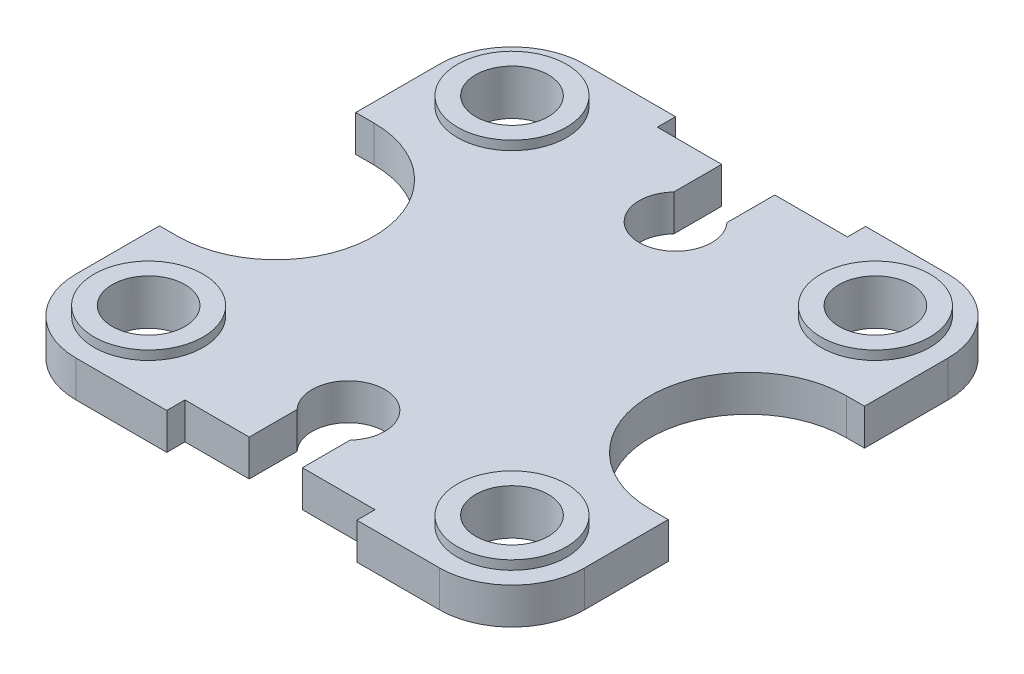
SolidWorks part; units mm, degrees
ref_plane "Front Plane" through (0, 0, 0) normal (0, 0, 1) x (1, 0, 0)
ref_plane "Top Plane" through (0, 0, 0) normal (0, 1, 0) x (1, 0, 0)
ref_plane "Right Plane" through (0, 0, 0) normal (1, 0, 0) x (0, 0, -1)
sketch "Sketch2" plane through (0, 0, 0) normal (0, 1, 0) x (1, 0, 0)
  line L0 (-169.9831, 0) -> (-150, 0) construction
  line L1 (-100, 140) -> (-50, 140)
  line L2 (-140, 100) -> (-140, 54)
  line L3 (-100, -140) -> (-50, -140)
  line L4 (140, 100) -> (140, 54)
  line L5 (-140, 140) -> (140, -140) construction
  line L6 (-140, -140) -> (140, 140) construction
  line L7 (-140, 0) -> (165.6353, 0) construction
  line L8 (-140, 54) -> (-130, 54)
  line L10 (-140, -54) -> (-130, -54)
  line L11 (-130, 54) -> (-130, 0)
  line L12 (-150, 54) -> (-130, -54) construction
  line L13 (-140, 0) -> (-130, 54) construction
  line L14 (-140, -54) -> (-140, -100)
  line L15 (0, 140) -> (0, -140) construction
  line L16 (140, -54) -> (130, -54)
  line L18 (140, 54) -> (130, 54)
  line L19 (140, -54) -> (140, -100)
  line L20 (54.6115, 140) -> (100, 140)
  line L22 (-50, 140) -> (-50, 130)
  line L23 (-50, 130) -> (-14.6115, 130)
  line L24 (54.6115, 140) -> (54.6115, 130)
  line L25 (-45.701, 148.3684) -> (54.6115, 130) construction
  line L26 (-50, 130) -> (54.2681, 150.8536) construction
  line L27 (14.6115, 130) -> (14.6115, 103.6567)
  line L28 (-14.6115, 130) -> (-14.6115, 103.6567)
  line L29 (54.6115, -140) -> (54.6115, -130)
  line L30 (-50, -140) -> (-50, -130)
  line L31 (-50, -130) -> (-14.6115, -130)
  line L32 (14.6115, -130) -> (14.6115, -103.6567)
  line L33 (-14.6115, -130) -> (-14.6115, -103.6567)
  line L34 (14.6115, 130) -> (54.6115, 130)
  line L35 (14.6115, -130) -> (54.6115, -130)
  line L36 (54.6115, -140) -> (100, -140)
  arc A0 (140, 100) -> (100, 140) centre (100, 100) ccw
  arc A1 (100, -140) -> (140, -100) centre (100, -100) ccw
  arc A2 (-100, -140) -> (-140, -100) centre (-100, -100) cw
  arc A3 (-100, 140) -> (-140, 100) centre (-100, 100) ccw
  arc A4 (-130, -54) -> (-130, 54) centre (-130, 0) ccw
  arc A5 (130, -54) -> (130, 54) centre (130, 0) cw
  circle A6 centre (-100, 100) radius 20
  circle A8 centre (100, 100) radius 20
  circle A9 centre (-100, -100) radius 20
  circle A10 centre (100, -100) radius 20
  arc A11 (-14.6115, 103.6567) -> (14.6115, 103.6567) centre (0, 90) ccw
  arc A12 (-14.6115, -103.6567) -> (14.6115, -103.6567) centre (0, -90) cw
  point P0 (0, 0)
  point P20 (-140, 0)
  dimension "D3" = 40
  dimension "D5" = 10
  dimension "D7" = 180
  dimension "D9" = 40
  dimension "D1" = 280
  dimension "D2" = 280
  dimension "D4" = 10
  dimension "D6" = 100
  dimension "D8" = 40
extrude "Boss-Extrude1" add sketch "Sketch2" along normal blind 20 contours L33 A12 L32 L35 L29 L36 A1 L19 L16 A5 L18 L4 A0 L20 L24 L34 L27 A11 L28 L23 L22 L1 A3 L2 L8 A4 L10 L14 A2 L3 L30 L31 A9 A6 A8 A10
sketch "Sketch3" plane through (0, 20, 0) normal (0, 1, 0) x (1, 0, 0)
  line L0 (0, 35.7741) -> (0, -24.3678) construction
  line L1 (-51.328, 0) -> (50.9824, 0) construction
  circle A0 centre (-100, 100) radius 30
  circle A1 centre (100, 100) radius 30
  circle A2 centre (100, -100) radius 30
  circle A3 centre (-100, -100) radius 30
  circle A4 centre (-100, 100) radius 20
  circle A5 centre (100, 100) radius 20
  circle A6 centre (100, -100) radius 20
  circle A7 centre (-100, -100) radius 20
  dimension "D1" = 60
extrude "Boss-Extrude2" add sketch "Sketch3" along normal blind 5
